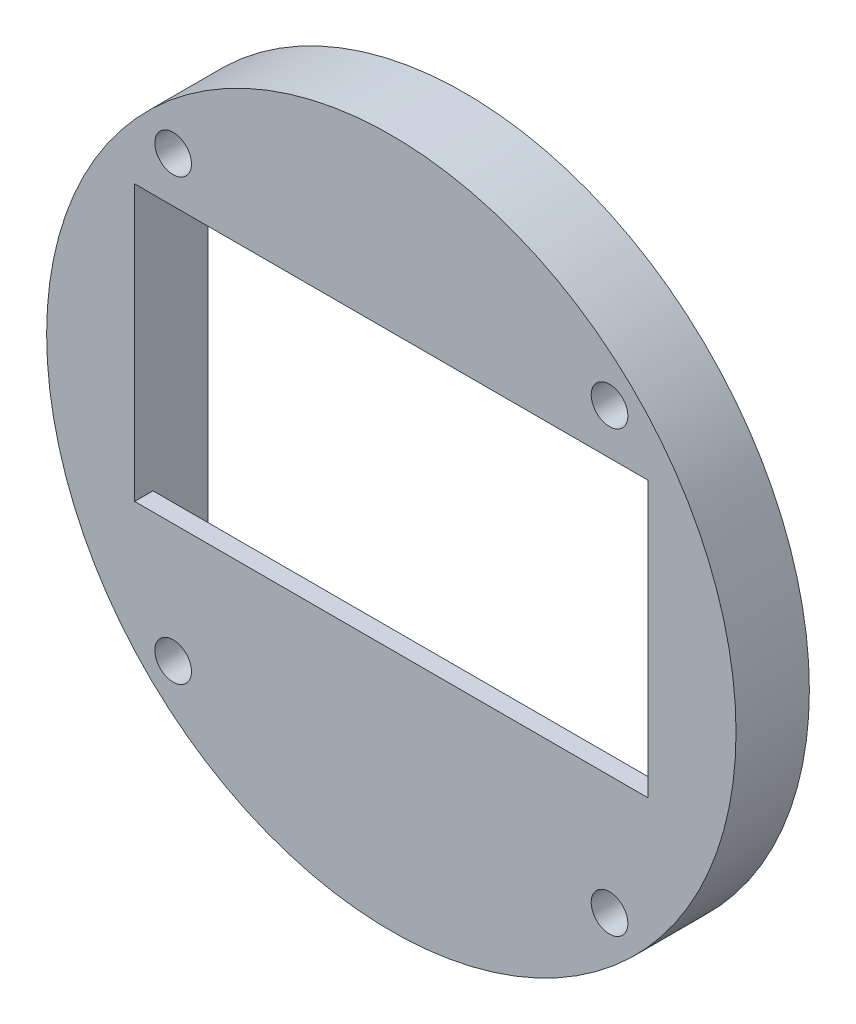
SolidWorks part; units mm, degrees
ref_plane "Front Plane" through (0, 0, 0) normal (0, 0, 1) x (1, 0, 0)
ref_plane "Top Plane" through (0, 0, 0) normal (0, 1, 0) x (1, 0, 0)
ref_plane "Right Plane" through (0, 0, 0) normal (1, 0, 0) x (0, 0, -1)
sketch "Sketch1" plane through (0, 0, 0) normal (0, 0, 1) x (1, 0, 0)
  line L0 (-11.9, 11.9856) -> (11.9, 11.9856) construction
  line L2 (14, -5.5) -> (14, 9.5)
  line L3 (14, 9.5) -> (-14, 9.5)
  line L4 (-14, -5.5) -> (-14, 9.5)
  line L5 (14, -9.5) -> (-14, 9.5) construction
  line L6 (14, 9.5) -> (-14, -9.5) construction
  line L7 (13.9, -14) -> (-13.9, -14) construction
  line L8 (13.9, -14) -> (13.9, 14) construction
  line L9 (12.5475, 14) -> (-13.9, 14) construction
  line L10 (-13.9, -14) -> (-13.9, 14) construction
  line L11 (13.9, -14) -> (-13.9, 14) construction
  line L12 (13.9, 14) -> (-13.9, -14) construction
  line L13 (11.9, 11.9856) -> (11.9, -11.9856) construction
  line L14 (11.9, -11.9856) -> (-11.9, -11.9856) construction
  line L15 (-11.9, -11.9856) -> (-11.9, 11.9856) construction
  line L16 (-14, -5.5) -> (14, -5.5)
  circle A1 centre (-11.9, 11.9856) radius 1
  circle A2 centre (11.9, 11.9856) radius 1
  circle A3 centre (11.9, -11.9856) radius 1
  circle A4 centre (-11.9, -11.9856) radius 1
  circle A5 centre (0, 0) radius 18.8
  dimension "D3" = 23.8
  dimension "D7" = 2
  dimension "D10" = 37.6
  dimension "D1" = 28
  dimension "D2" = 5.5
  dimension "D4" = 28
  dimension "D5" = 2
  dimension "D6" = 2.0144
  dimension "D8" = 15
  dimension "D9" = 14
extrude "Boss-Extrude1" add sketch "Sketch1" along normal blind 4
sketch "Sketch2" plane through (0, 0, 0) normal (0, 0, -1) x (-1, 0, 0)
  line L0 (-14, 9.5) -> (14, 9.5) construction
  line L1 (-14, 9.8) -> (-7, 9.8)
  line L2 (-14, 9.8) -> (-14, -10.1)
  line L3 (-14, -10.1) -> (-7, -10.1)
  line L4 (14, 9.8) -> (14, -10.1)
  line L5 (14, -5.5) -> (-14, -5.5) construction
  line L6 (14, 9.5) -> (14, -5.5) construction
  line L7 (-14, -5.5) -> (-14, 9.5) construction
  line L8 (7, 9.8) -> (14, 9.8)
  line L9 (7, -10.1) -> (14, -10.1)
  line L10 (-7, 9.8) -> (-7, 13.8)
  line L11 (-7, 13.8) -> (7, 13.8)
  line L12 (7, 9.8) -> (7, 13.8)
  line L14 (-7, -10.1) -> (-7, -14.1)
  line L15 (-7, -14.1) -> (7, -14.1)
  line L16 (7, -10.1) -> (7, -14.1)
  dimension "D1" = 0.3
  dimension "D2" = 4.6
  dimension "D3" = 4
  dimension "D4" = 14
  dimension "D5" = 7
  dimension "D6" = 14
  dimension "D7" = 4
extrude "Cut-Extrude1" cut sketch "Sketch2" against normal blind 3
fillet "Fillet1" radius 1 4 edges at (-7, 13.8, 1.5) (7, 13.8, 1.5) (7, -14.1, 1.5) (-7, -14.1, 1.5)
